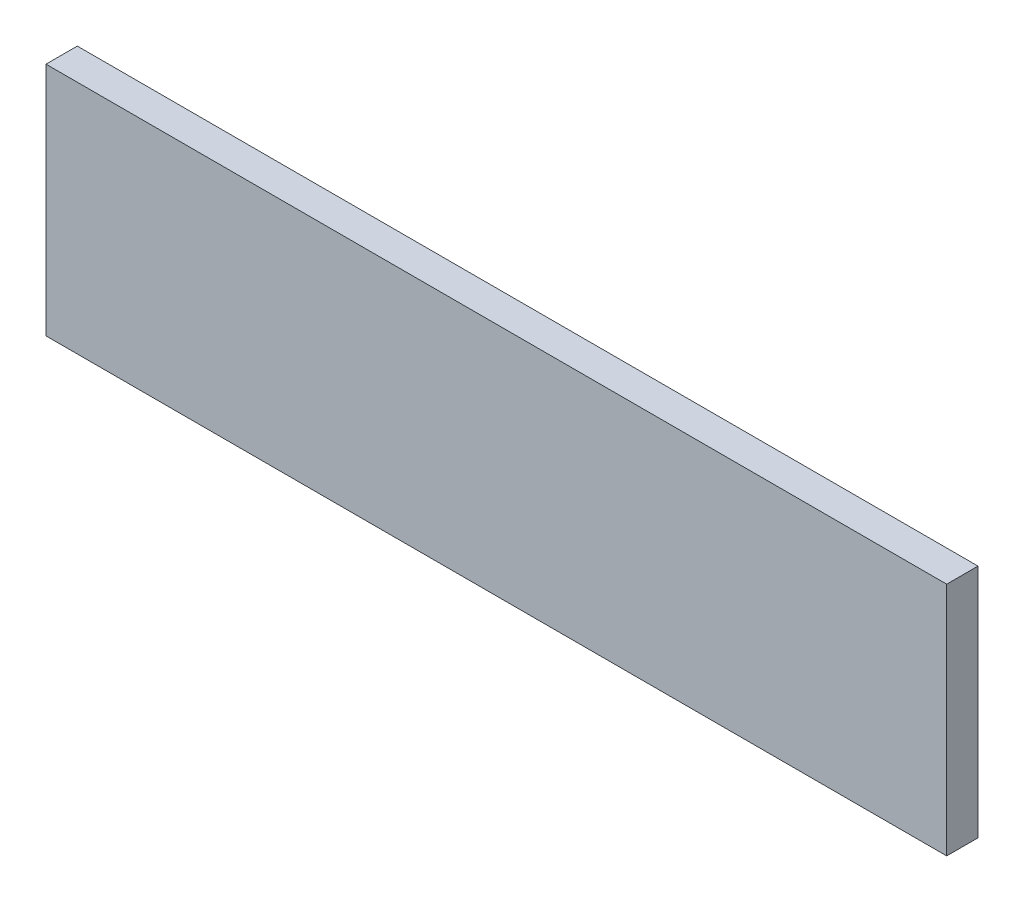
SolidWorks part; units mm, degrees
ref_plane "Front Plane" through (0, 0, 0) normal (0, 0, 1) x (1, 0, 0)
ref_plane "Top Plane" through (0, 0, 0) normal (0, 1, 0) x (1, 0, 0)
ref_plane "Right Plane" through (0, 0, 0) normal (1, 0, 0) x (0, 0, -1)
sketch "Sketch1" plane through (0, 0, 0) normal (0, 0, 1) x (1, 0, 0)
  line L1 (-33.7899, 21.4653) -> (110.0601, 21.4653)
  line L2 (-33.7899, 21.4653) -> (-33.7899, -16.1247)
  line L3 (-33.7899, -16.1247) -> (110.0601, -16.1247)
  line L4 (110.0601, 21.4653) -> (110.0601, -16.1247)
  dimension "D1" = 37.59
  dimension "D2" = 143.85
extrude "Boss-Extrude1" add sketch "Sketch1" along normal blind 5
